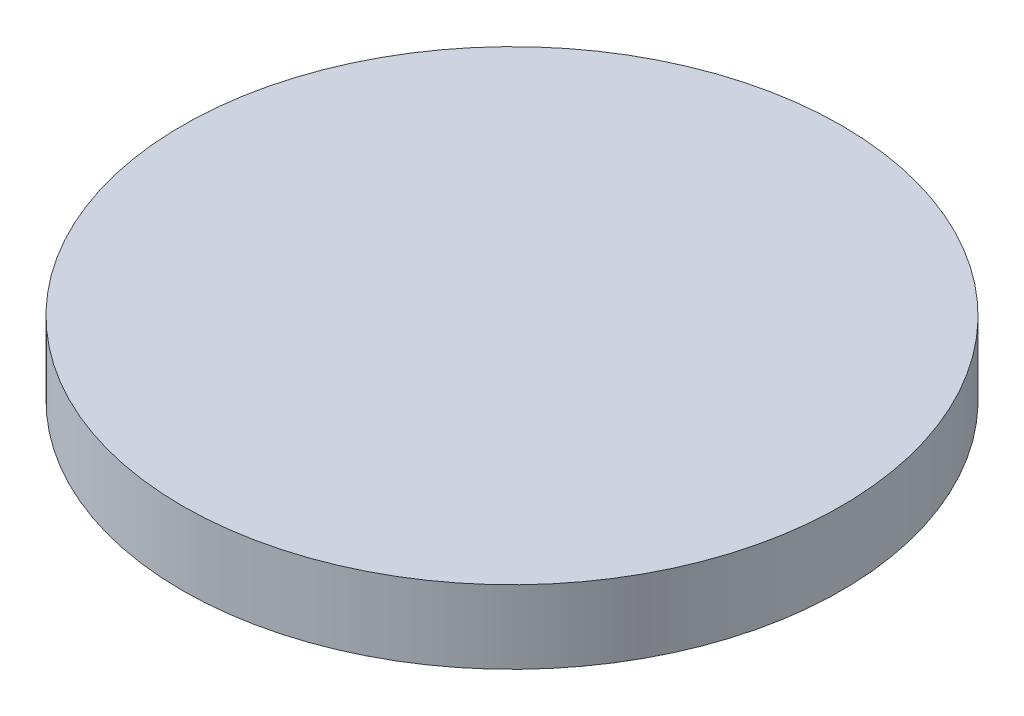
SolidWorks part; units mm, degrees
ref_plane "Front Plane" through (0, 0, 0) normal (0, 0, 1) x (1, 0, 0)
ref_plane "Top Plane" through (0, 0, 0) normal (0, 1, 0) x (1, 0, 0)
ref_plane "Right Plane" through (0, 0, 0) normal (1, 0, 0) x (0, 0, -1)
sketch "Sketch1" plane through (0, 0, 0) normal (0, 1, 0) x (1, 0, 0)
  circle A0 centre (0, 0) radius 85.725
  dimension "D1" = 171.45
extrude "Boss-Extrude1" add sketch "Sketch1" along normal blind 19.05
